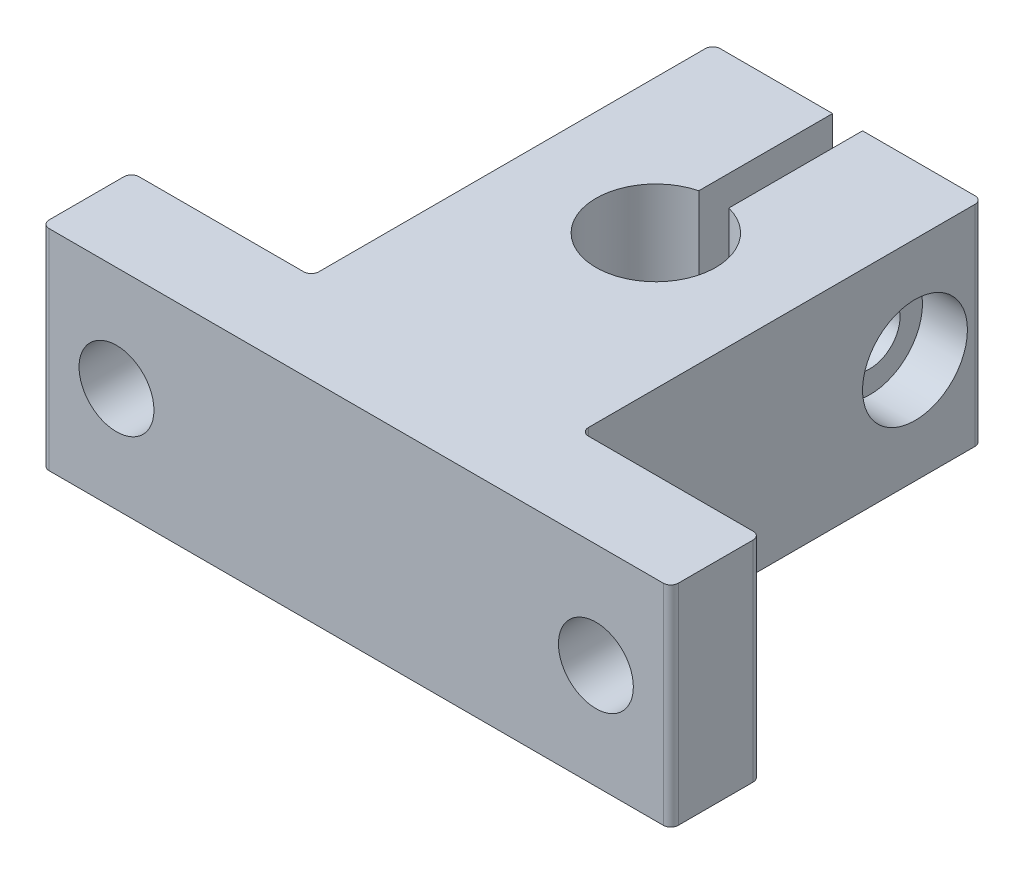
SolidWorks part; units mm, degrees
ref_plane "Front Plane" through (0, 0, 0) normal (0, 0, 1) x (1, 0, 0)
ref_plane "Top Plane" through (0, 0, 0) normal (0, 1, 0) x (1, 0, 0)
ref_plane "Right Plane" through (0, 0, 0) normal (1, 0, 0) x (0, 0, -1)
sketch "Sketch1" plane through (0, 0, 0) normal (0, 1, 0) x (1, 0, 0)
  line L0 (9, -14) -> (21, -14)
  line L1 (-21, -14) -> (-9, -14)
  line L2 (-21, -14) -> (-21, -20)
  line L3 (-21, -20) -> (21, -20)
  line L4 (21, -14) -> (21, -20)
  line L5 (-1, 12.8) -> (-1, 3.873)
  line L6 (-9, -14) -> (-9, 12.8)
  line L7 (-9, 12.8) -> (-1, 12.8)
  line L8 (9, -14) -> (9, 12.8)
  line L9 (1, 12.8) -> (1, 3.873)
  line L10 (1, 12.8) -> (9, 12.8)
  arc A0 (-1, 3.873) -> (1, 3.873) centre (0, 0) ccw
  point P8 (0, -20)
  dimension "D5" = 8
  dimension "D1" = 18
  dimension "D2" = 6
  dimension "D3" = 42
  dimension "D4" = 32.8
  dimension "D6" = 20
  dimension "D7" = 8
extrude "Boss-Extrude1" add sketch "Sketch1" along normal blind 14
sketch "Sketch2" plane through (9, 0, 0) normal (1, 0, 0) x (0, 0, -1)
  line L0 (12.8, 14) -> (12.8, 0) construction
  circle A0 centre (8.3, 7) radius 2
  dimension "D2" = 4
  dimension "D1" = 4.5
extrude "Cut-Extrude1" cut sketch "Sketch2" against normal blind 20
sketch "Sketch3" plane through (9, 0, 0) normal (1, 0, 0) x (0, 0, -1)
  circle A0 centre (8.3, 7) radius 3.5
  dimension "D1" = 7
extrude "Cut-Extrude2" cut sketch "Sketch3" against normal blind 3
sketch "Sketch4" plane through (0, 0, 20) normal (0, 0, 1) x (1, 0, 0)
  circle A0 centre (-16, 7) radius 2.5
  circle A1 centre (16, 7) radius 2.5
  dimension "D2" = 5
  dimension "D1" = 32
  dimension "D3" = 16
extrude "Cut-Extrude3" cut sketch "Sketch4" against normal blind 8
fillet "Fillet1" radius 0.5 8 edges at (9, 7, 14) (-9, 7, 14) (-9, 7, -12.8) (9, 7, -12.8) (21, 7, 14) (21, 7, 20) (-21, 7, 20) (-21, 7, 14)
